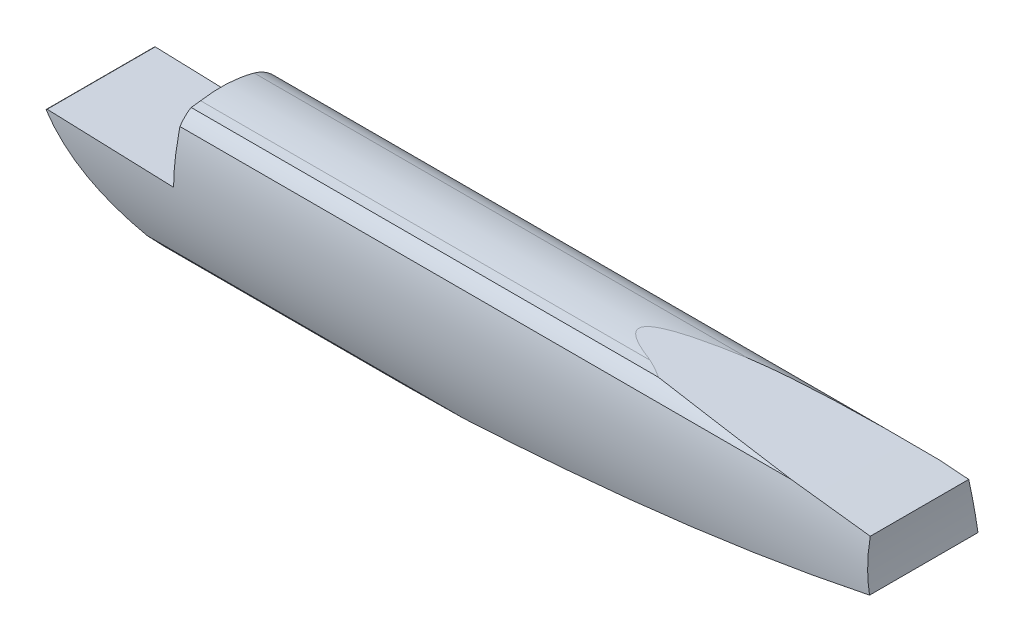
SolidWorks part; units mm, degrees
ref_plane "Front Plane" through (0, 0, 0) normal (0, 0, 1) x (1, 0, 0)
ref_plane "Top Plane" through (0, 0, 0) normal (0, 1, 0) x (1, 0, 0)
ref_plane "Right Plane" through (0, 0, 0) normal (1, 0, 0) x (0, 0, -1)
sketch "Sketch1" plane through (0, 0, 0) normal (0, 0, 1) x (1, 0, 0)
  arc A0 (-192.6294, 0) -> (-73.9915, 55.3217) centre (0.6853, -259.6942) cw
  arc A1 (-73.9915, 55.3217) -> (535.7856, 33.7196) centre (72.3044, -4432.1785) cw
  arc A2 (535.7856, 33.7196) -> (539.3178, -7.795) centre (823.0927, 37.2576) ccw
  arc A3 (539.3178, -7.795) -> (-66.5683, -71.6141) centre (-68.1444, 2851.3439) cw
  arc A4 (-192.6294, 0) -> (-66.5683, -71.6141) centre (-55.5394, 94.5588) ccw
  point P9 (538.8762, -8.7043)
  point P11 (539.3178, -7.795)
  point P12 (0, 0)
extrude "Boss-Extrude1" add sketch "Sketch1" along normal blind 100
sketch "Sketch2" plane through (0, 0, 0) normal (1, 0, 0) x (0, 0, -1)
  arc A0 (-65.4472, 54.8304) -> (-92.9565, 40.6004) centre (-65.0756, 20.4068) ccw
  arc A1 (-92.9565, 40.6004) -> (-88.9673, -61.9502) centre (74.239, -4.2486) ccw
  arc A2 (-88.9673, -61.9502) -> (-75.5891, -72.2161) centre (-66.8398, -46.9643) ccw
  arc A3 (-75.5891, -72.2161) -> (-173.3785, -75.4078) centre (-126.0797, -24.9172) cw
  arc A4 (-173.3785, -75.4078) -> (-135.2629, 60.9401) centre (86.0317, -74.4236) cw
  arc A5 (-135.2629, 60.9401) -> (-61.3269, 89.0039) centre (-51.8166, -47.4784) cw
  arc A6 (-61.3269, 89.0039) -> (-65.4472, 54.8304) centre (778.5841, -29.5983) ccw
  point P14 (-92.9565, 40.6004)
  point P15 (-92.9565, -52.6319)
extrude "Cut-Extrude3" cut sketch "Sketch2" against normal through all both and the other way through all
sketch "Sketch3" plane through (0, 0, 0) normal (1, 0, 0) x (0, 0, -1)
  arc A0 (-74.2083, 50.8866) -> (-26.7131, 48.511) centre (-56.0106, -61.2597) cw
  arc A1 (-26.7131, 48.511) -> (-7.715, 36.1895) centre (-36.3575, 12.8336) cw
  arc A2 (-8.6781, -61.6499) -> (-29.5113, -74.3603) centre (-30.579, -49.1815) cw
  arc A3 (-74.2083, 50.8866) -> (12.3195, 83.1167) centre (-99.8212, 251.9147) cw
  arc A4 (12.3195, 83.1167) -> (85.2864, -42.1041) centre (302.1155, 168.113) ccw
  arc A5 (85.2864, -42.1041) -> (-29.5113, -74.3603) centre (9.4865, 7.2561) cw
  arc A6 (-7.715, 36.1895) -> (-8.6781, -61.6499) centre (-213.3664, -10.7106) cw
  point P14 (-74.2083, 50.8866)
extrude "Cut-Extrude5" cut sketch "Sketch3" against normal through all both and the other way through all
sketch "Sketch4" plane through (0, 0, 0) normal (0, 0, 1) x (1, 0, 0)
  line L0 (-79.2014, 32.882) -> (-79.2014, -3.1227)
  line L1 (-79.2014, -3.1227) -> (-222.7681, 1.8142)
  line L2 (-222.7681, 1.8142) -> (-233.2223, 17.1102)
  line L3 (-233.2223, 17.1102) -> (-80.5294, 72.4569)
  line L4 (-80.5294, 72.4569) -> (-79.2014, 32.882)
  point P2 (-88.013, 30.0119)
  point P6 (-84.8201, 71.766)
  point P7 (-80.5294, 32.882)
  point P8 (-80.5294, 72.4569)
  point P9 (-79.2014, -3.1227)
extrude "Cut-Extrude7" cut sketch "Sketch4" against normal through all both and the other way through all
